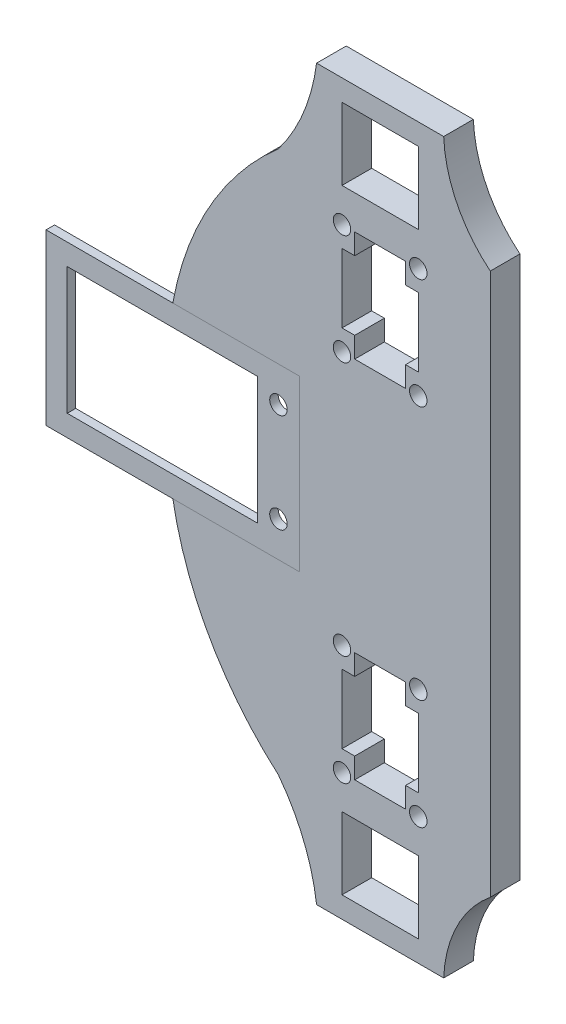
SolidWorks part; units mm, degrees
ref_plane "Front Plane" through (0, 0, 0) normal (1, 0, 0) x (0, 1, 0)
ref_plane "Top Plane" through (0, 0, 0) normal (0, 0, 1) x (0, 1, 0)
ref_plane "Right Plane" through (0, 0, 0) normal (0, 1, 0) x (-1, 0, 0)
sketch "Sketch1" plane through (0, 0, 0) normal (0, 0, 1) x (0, 1, 0)
  line L0 (0, 10.6597) -> (0, -17.5494) construction
  line L1 (-11.685, 13.7811) -> (11.685, 13.7811) construction
  line L2 (-15, 18.7811) -> (15, 18.7811)
  line L3 (-20, 8.7811) -> (20, 8.7811)
  line L4 (-20, 8.7811) -> (-20, 68.6311)
  line L5 (-20, 68.6311) -> (20, 68.6311)
  line L6 (20, 68.6311) -> (20, 8.7811)
  line L7 (-15, 65.2311) -> (15, 65.2311) construction
  line L8 (-15, 18.7811) -> (-15, 63.6311)
  line L9 (-15, 63.6311) -> (15, 63.6311)
  line L10 (15, 63.6311) -> (15, 18.7811)
  circle A0 centre (-11.685, 13.7811) radius 2.06
  circle A1 centre (11.685, 13.7811) radius 2.06
  circle A2 centre (-15, 65.2311) radius 1.6 construction
  circle A3 centre (15, 65.2311) radius 1.6 construction
  point P5 (0, 13.7811)
  point P10 (0, 18.7811)
  point P11 (0, 8.7811)
  point P18 (0, 65.2311)
  dimension "D2" = 4.12
  dimension "D7" = 3.2
  dimension "D1" = 23.37
  dimension "D3" = 5
  dimension "D4" = 5
  dimension "D5" = 30
  dimension "D6" = 40
  dimension "D8" = 51.45
  dimension "D9" = 5
extrude "Boss-Extrude2" add sketch "Sketch1" along normal blind 2 contours L6 L5 L4 L3 L9 L10 L2 L8 A0 A1
sketch "Sketch2" plane through (0, 0, 2) normal (0, 0, 1) x (1, 0, 0)
  line L0 (-68.6311, 0) -> (-8.7811, 0) construction
  line L1 (-68.6311, -20) -> (-68.6311, 20) construction
  line L2 (-8.7811, -20) -> (-8.7811, 20) construction
  line L3 (-13.7811, 11.685) -> (-13.7811, 0) construction
  line L4 (-68.6311, 20) -> (-8.7811, 20) construction
  line L5 (-13.7811, 0) -> (36.2189, 0)
  line L6 (-13.7811, -64) -> (-13.7811, 64)
  line L7 (-13.7811, 64) -> (36.2189, 64)
  line L8 (36.2189, -64) -> (36.2189, 64)
  line L9 (10.2189, 30) -> (10.2189, 56) construction
  line L10 (1.2189, 56) -> (19.2189, 56) construction
  line L11 (1.2189, 56) -> (1.2189, 30) construction
  line L12 (1.2189, 30) -> (19.2189, 30) construction
  line L13 (19.2189, 56) -> (19.2189, 30) construction
  line L14 (1.2189, 43) -> (19.2189, 43) construction
  line L15 (1.2189, 51.1325) -> (4.2189, 51.1325)
  line L16 (4.2189, 51.1325) -> (4.2189, 56)
  line L17 (1.2189, 51.1325) -> (1.2189, 34.8675)
  line L18 (4.2189, 56) -> (16.2189, 56)
  line L19 (19.2189, 51.1325) -> (19.2189, 34.8675)
  line L20 (19.2189, 51.1325) -> (16.2189, 51.1325)
  line L21 (16.2189, 51.1325) -> (16.2189, 56)
  line L22 (16.2189, 34.8675) -> (16.2189, 30)
  line L23 (19.2189, 34.8675) -> (16.2189, 34.8675)
  line L24 (1.2189, 34.8675) -> (4.2189, 34.8675)
  line L25 (4.2189, 30) -> (16.2189, 30)
  line L26 (4.2189, 34.8675) -> (4.2189, 30)
  line L27 (1.2189, 81) -> (19.2189, 81)
  line L28 (-4.7811, 86) -> (25.2189, 86)
  line L29 (10.2189, 56) -> (10.2189, 91.8567) construction
  line L30 (1.2189, 81) -> (1.2189, 56)
  line L31 (19.2189, 81) -> (19.2189, 56)
  line L32 (10.2189, -56) -> (10.2189, -91.8567) construction
  line L33 (1.2189, -43) -> (19.2189, -43) construction
  line L34 (19.2189, -56) -> (19.2189, -30) construction
  line L35 (1.2189, -30) -> (19.2189, -30) construction
  line L36 (1.2189, -56) -> (1.2189, -30) construction
  line L37 (1.2189, -56) -> (19.2189, -56) construction
  line L38 (10.2189, -30) -> (10.2189, -56) construction
  line L39 (19.2189, -81) -> (19.2189, -56)
  line L40 (1.2189, -81) -> (1.2189, -56)
  line L41 (-4.7811, -86) -> (25.2189, -86)
  line L42 (1.2189, -81) -> (19.2189, -81)
  line L43 (4.2189, -34.8675) -> (4.2189, -30)
  line L44 (4.2189, -30) -> (16.2189, -30)
  line L45 (1.2189, -34.8675) -> (4.2189, -34.8675)
  line L46 (19.2189, -34.8675) -> (16.2189, -34.8675)
  line L47 (16.2189, -34.8675) -> (16.2189, -30)
  line L48 (16.2189, -51.1325) -> (16.2189, -56)
  line L49 (19.2189, -51.1325) -> (16.2189, -51.1325)
  line L50 (19.2189, -51.1325) -> (19.2189, -34.8675)
  line L51 (4.2189, -56) -> (16.2189, -56)
  line L52 (1.2189, -51.1325) -> (1.2189, -34.8675)
  line L53 (4.2189, -51.1325) -> (4.2189, -56)
  line L54 (1.2189, -51.1325) -> (4.2189, -51.1325)
  line L55 (-13.7811, -64) -> (36.2189, -64)
  circle A0 centre (1.2189, 56) radius 2.06
  circle A1 centre (19.2189, 56) radius 2.06
  circle A2 centre (1.2189, 30) radius 2.06
  circle A3 centre (19.2189, 30) radius 2.06
  arc A4 (-38.7061, 20) -> (-13.7811, 64) centre (36.2189, 6.6164) cw
  arc A5 (-13.7811, 64) -> (-4.7811, 86) centre (-50.4864, 91.8567) ccw
  arc A6 (25.2189, 86) -> (36.2189, 64) centre (55.1934, 87.2372) ccw
  arc A7 (25.2189, -86) -> (36.2189, -64) centre (55.1934, -87.2372) cw
  arc A8 (-13.7811, -64) -> (-4.7811, -86) centre (-50.4864, -91.8567) cw
  arc A9 (-38.7061, -20) -> (-13.7811, -64) centre (36.2189, -6.6164) ccw
  circle A10 centre (19.2189, -30) radius 2.06
  circle A11 centre (1.2189, -30) radius 2.06
  circle A12 centre (19.2189, -56) radius 2.06
  circle A13 centre (1.2189, -56) radius 2.06
  point P12 (-38.7061, 20)
  point P45 (10.2189, 81)
  point P46 (10.2189, 86)
  point P85 (10.2189, -86)
  point P86 (10.2189, -81)
  point P87 (-38.7061, -20)
  dimension "D3" = 4.12
  dimension "D14" = 30
  dimension "D1" = 18
  dimension "D2" = 26
  dimension "D4" = 3
  dimension "D5" = 4.8675
  dimension "D6" = 15
  dimension "D7" = 30
  dimension "D8" = 8
  dimension "D9" = 50
  dimension "D10" = 18
  dimension "D11" = 25
  dimension "D12" = 5
  dimension "D13" = 30
extrude "Boss-Extrude3" add sketch "Sketch2" against normal blind 7 separate body
